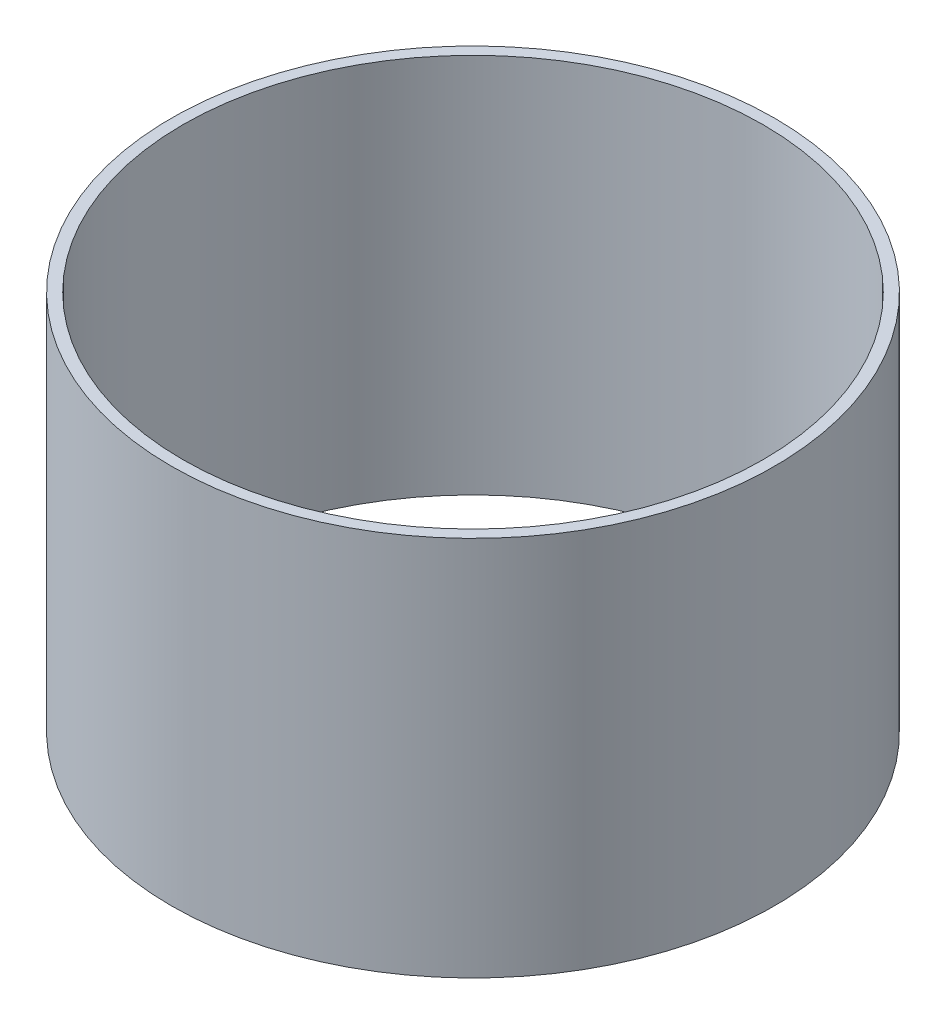
SolidWorks part; units mm, degrees
ref_plane "Front Plane" through (0, 0, 0) normal (0, 0, 1) x (1, 0, 0)
ref_plane "Top Plane" through (0, 0, 0) normal (0, 1, 0) x (1, 0, 0)
ref_plane "Right Plane" through (0, 0, 0) normal (1, 0, 0) x (0, 0, -1)
sketch "Sketch1" plane through (0, 0, 0) normal (0, 1, 0) x (1, 0, 0)
  circle A0 centre (0, 0) radius 39.6
  circle A1 centre (0, 0) radius 38.1
  dimension "D1" = 79.2
  dimension "D2" = 76.2
extrude "Boss-Extrude1" add sketch "Sketch1" along normal blind 50
